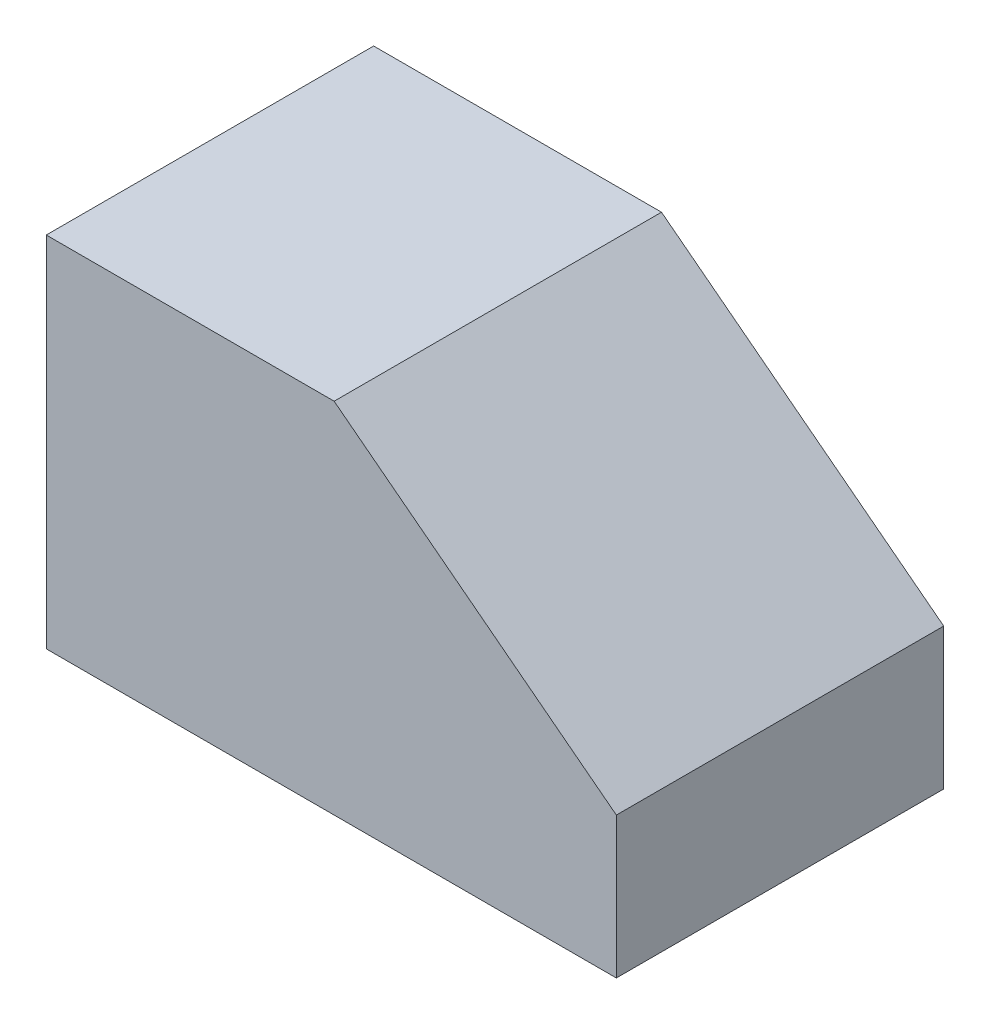
SolidWorks part; units mm, degrees
ref_plane "Front Plane" through (0, 0, 0) normal (0, 0, 1) x (1, 0, 0)
ref_plane "Top Plane" through (0, 0, 0) normal (0, 1, 0) x (1, 0, 0)
ref_plane "Right Plane" through (0, 0, 0) normal (1, 0, 0) x (0, 0, -1)
sketch "Sketch1" plane through (0, 0, 0) normal (0, 0, 1) x (1, 0, 0)
  line L0 (0, 0) -> (101, 0)
  line L1 (101, 0) -> (101, 25)
  line L2 (101, 25) -> (51, 63.5)
  line L3 (51, 63.5) -> (0, 63.5)
  line L4 (0, 63.5) -> (0, 0)
  point P7 (0, 0)
  dimension "D1" = 101
  dimension "D2" = 25
  dimension "D3" = 63.5
  dimension "D4" = 51
extrude "Boss-Extrude1" add sketch "Sketch1" along normal mid plane 58
sketch3d "3DSketch1"
  line L0 (0, 63.5, 29) -> (0, 63.5, 9.95)
  line L1 (0, 63.5, 29) -> (0, 63.5, -29) construction
  line L2 (0, 63.5, 9.95) -> (19.05, 63.5, 29)
  line L3 (51, 63.5, 29) -> (0, 63.5, 29) construction
  line L4 (19.05, 63.5, 29) -> (0, 63.5, 29)
  line L5 (9.525, 63.5, 19.475) -> (0, 38.1, 29) construction
  line L6 (0, 63.5, 29) -> (0, 0, 29) construction
  dimension "D1" = 19.05
  dimension "D2" = 25.4
